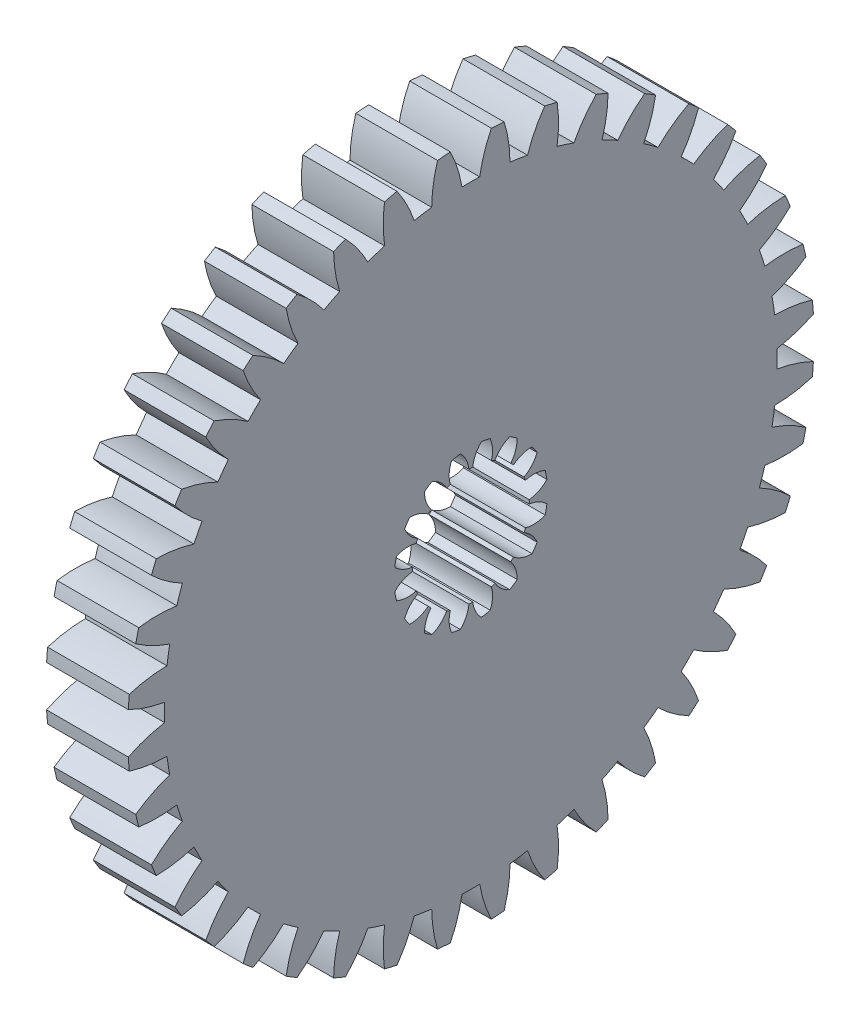
SolidWorks part; units mm, degrees
ref_plane "Plane1" through (0, 0, 0) normal (0, 0, 1) x (1, 0, 0)
ref_plane "Plane2" through (0, 0, 0) normal (0, 1, 0) x (1, 0, 0)
ref_plane "Plane3" through (0, 0, 0) normal (1, 0, 0) x (0, 0, -1)
sketch "HoldingSke" plane through (0, 0, 0) normal (0, 1, 0) x (1, 0, 0)
  line L0 (0, 0) -> (0.766, -0.6428)
  line L1 (-15, 0) -> (100, 0) construction
  line L2 (0, 0) -> (-2.1039, 2.3779)
  line L3 (0, 0) -> (-11.863, 4.5341)
  line L4 (0, 0) -> (6.6156, 5.5511)
  line L5 (0, 0) -> (-46.8476, -17.4728)
  line L6 (0, 0) -> (-4.1448, -2.7965)
  line L7 (-2.1039, 2.3779) -> (8.6586, 51.2059)
  line L8 (-76.2, 54.61) -> (-75.9, 54.61)
  line L9 (-67.7845, 28.3722) -> (-49.3413, 33.142)
  line L10 (-76.2, 71.12) -> (104.1128, 71.12)
  line L11 (0, 0) -> (-5, 0)
  line L12 (-76.2, 101.6) -> (-76.162, 101.6)
  line L13 (24.9733, 27.94) -> (52.9518, 28.4284)
  line L14 (24.9733, 27.94) -> (24.9743, 27.94)
  line L15 (24.9733, 27.94) -> (100.4006, 29.5858)
  line L16 (-63.627, -1) -> (-12.827, -1)
  circle A0 centre (0, 0) radius 1
  circle A1 centre (0, 0) radius 18.749
  circle A2 centre (0, 0) radius 37.5
  circle A3 centre (0, 0) radius 1
  dimension "MHD" = 37.498
  dimension "Hub_dia" = 75
  dimension "Bore" = 2
  dimension "MBD" = 2
  dimension "Num_teeth" = 40
  dimension "Pitch" = 1
  dimension "Overall_len" = 50
  dimension "Show_teeth" = 40
  dimension "Thickness" = 5
  dimension "OAL" = 50.0001
  dimension "T_dim" = 0.3
  dimension "Ap" = 14.5
  dimension "H" = 19.05
  dimension "Pitch_radius" = 180.3128
  dimension "Width" = 5
  dimension "Backlash" = 0.038
  dimension "Addendum_fac" = 1
  dimension "Dedendum_fac" = 1.25
  dimension "Clearance_fac" = 0.25
  dimension "Dedendum_add" = 0.001
  dimension "Module" = 1
sketch "BasProSke" plane through (0, 0, 0) normal (0, 1, 0) x (1, 0, 0)
  line L0 (-10, 0) -> (60, 0) construction
  line L1 (0, 0) -> (0, 21)
  line L2 (0, 0) -> (5, 0)
  line L3 (5, 0) -> (5, 21)
  line L4 (5, 21) -> (0, 21)
  dimension "Thickness" = 5
  dimension "Diameter" = 42
revolve "Base-Revolve" add sketch "BasProSke" angle 360 about L0
sketch "TooCutSke" plane through (0, 0, 0) normal (1, 0, 0) x (0, 0, -1)
  line L1 (0, 0) -> (0, 107) construction
  line L2 (0, 0) -> (-0.8517, 19.9819) construction
  line L3 (0, 0) -> (-3.1363, 39.8509) construction
  line L4 (-0.8517, 19.9819) -> (-1.5682, 19.9255) construction
  arc A0 (0.5419, 18.7412) -> (-0.5419, 18.7412) centre (0, 0) ccw
  arc A1 (1.2681, 20.9871) -> (-1.2681, 20.9871) centre (0, 0) ccw
  circle A2 centre (0, 0) radius 20 construction
  circle A3 centre (0, 0) radius 19.363 construction
  arc A4 (-0.5419, 18.7412) -> (-1.2681, 20.9871) centre (-8.4337, 17.4298) ccw
  arc A5 (1.2681, 20.9871) -> (0.5419, 18.7412) centre (8.4337, 17.4298) ccw
  dimension "Root_dia" = 37.498
  dimension "Overcut_dia" = 42.0508
  dimension "Pitch_dia" = 40
  dimension "Base_dia" = 38.7259
  dimension "Flank_rad" = 8
  dimension "Half_ang" = 4.5
  dimension "Half_CT" = 0.7187
extrude "ToothCut" cut sketch "TooCutSke" along normal through all
fillet "Breaks" [suppressed] radius 0.02
fillet "RootFillets" [suppressed] radius 0.251
pattern_circular "TeethCuts" count 40 every 9 about axis through (-10, 0, 0) along (1, 0, 0) of "ToothCut", "RootFillets", "Breaks"
sketch "HubNeaOneSke" plane through (0, 0, 0) normal (-1, 0, 0) x (0, 0, 1)
  circle A0 centre (0, 0) radius 18.749
  dimension "Diameter" = 37.498
extrude "HubNearOne" [suppressed] add sketch "HubNeaOneSke" along normal blind 45.0001
sketch "HubNeaBotSke" plane through (0, 0, 0) normal (-1, 0, 0) x (0, 0, 1)
  circle A0 centre (0, 0) radius 18.749
  dimension "Diameter" = 37.498
extrude "HubNearBoth" [suppressed] add sketch "HubNeaBotSke" along normal blind 22.5
ref_plane "FarPln" through (5, 0, 0) normal (1, 0, 0) x (0, 0, -1)
sketch "HubFarSke" plane through (5, 0, 0) normal (1, 0, 0) x (0, 0, -1)
  circle A0 centre (0, 0) radius 18.749
  dimension "Diameter" = 37.498
extrude "HubFar" [suppressed] add sketch "HubFarSke" along normal blind 22.5
sketch "BorSke" plane through (0, 0, 0) normal (1, 0, 0) x (0, 0, -1)
  circle A0 centre (0, 0) radius 1
  dimension "Diameter" = 2
extrude "Bore" cut sketch "BorSke" along normal mid plane 100.0001
sketch "KeySke" plane through (0, 0, 0) normal (1, 0, 0) x (0, 0, -1)
  line L0 (-0.4, 0) -> (-0.4, 1.3)
  line L1 (-0.4, 1.3) -> (0.4, 1.3)
  line L2 (0.4, 1.3) -> (0.4, 0)
  line L3 (0, 0) -> (0, 34) construction
  line L4 (-0.4, 0) -> (0.4, 0)
  dimension "Offset" = 1.3
  dimension "Width" = 0.8
extrude "Keyway" [suppressed] cut sketch "KeySke" along normal mid plane 100.0001
pattern_circular "Keyway2" [suppressed] count 2 every 90 about axis through (-10, 0, 0) along (1, 0, 0)
sketch "Schizzo2" plane through (5, 0, 0) normal (1, 0, 0) x (0, 0, -1)
  arc A64 (-0.1172, 3.5721) -> (-0.645, 4.6555) centre (-1.906, 3.3711) ccw
  arc A65 (0.1172, 3.5721) -> (-0.1172, 3.5721) centre (0, 0) ccw
  arc A66 (0.645, 4.6555) -> (0.1172, 3.5721) centre (1.906, 3.3711) ccw
  arc A67 (1.1857, 4.548) -> (0.645, 4.6555) centre (0, 0) ccw
  arc A68 (1.2587, 3.345) -> (1.1857, 4.548) centre (-0.4708, 3.8439) ccw
  arc A69 (1.4753, 3.2553) -> (1.2587, 3.345) centre (0, 0) ccw
  arc A70 (2.3775, 4.0543) -> (1.4753, 3.2553) centre (3.051, 2.3851) ccw
  arc A71 (2.8359, 3.748) -> (2.3775, 4.0543) centre (0, 0) ccw
  arc A72 (2.4429, 2.6087) -> (2.8359, 3.748) centre (1.036, 3.7314) ccw
  arc A73 (2.6087, 2.4429) -> (2.4429, 2.6087) centre (0, 0) ccw
  arc A74 (3.748, 2.8359) -> (2.6087, 2.4429) centre (3.7314, 1.036) ccw
  arc A75 (4.0543, 2.3775) -> (3.748, 2.8359) centre (0, 0) ccw
  arc A76 (3.2553, 1.4753) -> (4.0543, 2.3775) centre (2.3851, 3.051) ccw
  arc A77 (3.345, 1.2587) -> (3.2553, 1.4753) centre (0, 0) ccw
  arc A78 (4.548, 1.1857) -> (3.345, 1.2587) centre (3.8439, -0.4708) ccw
  arc A79 (4.6555, 0.645) -> (4.548, 1.1857) centre (0, 0) ccw
  arc A80 (3.5721, 0.1172) -> (4.6555, 0.645) centre (3.3711, 1.906) ccw
  arc A81 (3.5721, -0.1172) -> (3.5721, 0.1172) centre (0, 0) ccw
  arc A82 (4.6555, -0.645) -> (3.5721, -0.1172) centre (3.3711, -1.906) ccw
  arc A83 (4.548, -1.1857) -> (4.6555, -0.645) centre (0, 0) ccw
  arc A84 (3.345, -1.2587) -> (4.548, -1.1857) centre (3.8439, 0.4708) ccw
  arc A85 (3.2553, -1.4753) -> (3.345, -1.2587) centre (0, 0) ccw
  arc A86 (4.0543, -2.3775) -> (3.2553, -1.4753) centre (2.3851, -3.051) ccw
  arc A87 (3.748, -2.8359) -> (4.0543, -2.3775) centre (0, 0) ccw
  arc A88 (2.6087, -2.4429) -> (3.748, -2.8359) centre (3.7314, -1.036) ccw
  arc A89 (2.4429, -2.6087) -> (2.6087, -2.4429) centre (0, 0) ccw
  arc A90 (2.8359, -3.748) -> (2.4429, -2.6087) centre (1.036, -3.7314) ccw
  arc A91 (2.3775, -4.0543) -> (2.8359, -3.748) centre (0, 0) ccw
  arc A92 (1.4753, -3.2553) -> (2.3775, -4.0543) centre (3.051, -2.3851) ccw
  arc A93 (1.2587, -3.345) -> (1.4753, -3.2553) centre (0, 0) ccw
  arc A94 (1.1857, -4.548) -> (1.2587, -3.345) centre (-0.4708, -3.8439) ccw
  arc A95 (0.645, -4.6555) -> (1.1857, -4.548) centre (0, 0) ccw
  arc A96 (0.1172, -3.5721) -> (0.645, -4.6555) centre (1.906, -3.3711) ccw
  arc A97 (-0.1172, -3.5721) -> (0.1172, -3.5721) centre (0, 0) ccw
  arc A98 (-0.645, -4.6555) -> (-0.1172, -3.5721) centre (-1.906, -3.3711) ccw
  arc A99 (-1.1857, -4.548) -> (-0.645, -4.6555) centre (0, 0) ccw
  arc A100 (-1.2587, -3.345) -> (-1.1857, -4.548) centre (0.4708, -3.8439) ccw
  arc A101 (-1.4753, -3.2553) -> (-1.2587, -3.345) centre (0, 0) ccw
  arc A102 (-2.3775, -4.0543) -> (-1.4753, -3.2553) centre (-3.051, -2.3851) ccw
  arc A103 (-2.8359, -3.748) -> (-2.3775, -4.0543) centre (0, 0) ccw
  arc A104 (-2.4429, -2.6087) -> (-2.8359, -3.748) centre (-1.036, -3.7314) ccw
  arc A105 (-2.6087, -2.4429) -> (-2.4429, -2.6087) centre (0, 0) ccw
  arc A106 (-3.748, -2.8359) -> (-2.6087, -2.4429) centre (-3.7314, -1.036) ccw
  arc A107 (-4.0543, -2.3775) -> (-3.748, -2.8359) centre (0, 0) ccw
  arc A108 (-3.2553, -1.4753) -> (-4.0543, -2.3775) centre (-2.3851, -3.051) ccw
  arc A109 (-3.345, -1.2587) -> (-3.2553, -1.4753) centre (0, 0) ccw
  arc A110 (-4.548, -1.1857) -> (-3.345, -1.2587) centre (-3.8439, 0.4708) ccw
  arc A111 (-4.6555, -0.645) -> (-4.548, -1.1857) centre (0, 0) ccw
  arc A112 (-3.5721, -0.1172) -> (-4.6555, -0.645) centre (-3.3711, -1.906) ccw
  arc A113 (-3.5721, 0.1172) -> (-3.5721, -0.1172) centre (0, 0) ccw
  arc A114 (-4.6555, 0.645) -> (-3.5721, 0.1172) centre (-3.3711, 1.906) ccw
  arc A115 (-4.548, 1.1857) -> (-4.6555, 0.645) centre (0, 0) ccw
  arc A116 (-3.345, 1.2587) -> (-4.548, 1.1857) centre (-3.8439, -0.4708) ccw
  arc A117 (-3.2553, 1.4753) -> (-3.345, 1.2587) centre (0, 0) ccw
  arc A118 (-4.0543, 2.3775) -> (-3.2553, 1.4753) centre (-2.3851, 3.051) ccw
  arc A119 (-3.748, 2.8359) -> (-4.0543, 2.3775) centre (0, 0) ccw
  arc A120 (-2.6087, 2.4429) -> (-3.748, 2.8359) centre (-3.7314, 1.036) ccw
  arc A121 (-2.4429, 2.6087) -> (-2.6087, 2.4429) centre (0, 0) ccw
  arc A122 (-2.8359, 3.748) -> (-2.4429, 2.6087) centre (-1.036, 3.7314) ccw
  arc A123 (-2.3775, 4.0543) -> (-2.8359, 3.748) centre (0, 0) ccw
  arc A124 (-1.4753, 3.2553) -> (-2.3775, 4.0543) centre (-3.051, 2.3851) ccw
  arc A125 (-1.2587, 3.345) -> (-1.4753, 3.2553) centre (0, 0) ccw
  arc A126 (-1.1857, 4.548) -> (-1.2587, 3.345) centre (0.4708, 3.8439) ccw
  arc A127 (-0.645, 4.6555) -> (-1.1857, 4.548) centre (0, 0) ccw
  arc A128 (-0.1172, 3.5721) -> (-0.645, 4.6555) centre (-1.906, 3.3711) ccw
  arc A129 (0.1172, 3.5721) -> (-0.1172, 3.5721) centre (0, 0) ccw
  arc A130 (0.645, 4.6555) -> (0.1172, 3.5721) centre (1.906, 3.3711) ccw
  arc A131 (1.1857, 4.548) -> (0.645, 4.6555) centre (0, 0) ccw
  arc A132 (1.2587, 3.345) -> (1.1857, 4.548) centre (-0.4708, 3.8439) ccw
  arc A133 (1.4753, 3.2553) -> (1.2587, 3.345) centre (0, 0) ccw
  arc A134 (2.3775, 4.0543) -> (1.4753, 3.2553) centre (3.051, 2.3851) ccw
  arc A135 (2.8359, 3.748) -> (2.3775, 4.0543) centre (0, 0) ccw
  arc A136 (2.4429, 2.6087) -> (2.8359, 3.748) centre (1.036, 3.7314) ccw
  arc A137 (2.6087, 2.4429) -> (2.4429, 2.6087) centre (0, 0) ccw
  arc A138 (3.748, 2.8359) -> (2.6087, 2.4429) centre (3.7314, 1.036) ccw
  arc A139 (4.0543, 2.3775) -> (3.748, 2.8359) centre (0, 0) ccw
  arc A140 (3.2553, 1.4753) -> (4.0543, 2.3775) centre (2.3851, 3.051) ccw
  arc A141 (3.345, 1.2587) -> (3.2553, 1.4753) centre (0, 0) ccw
  arc A142 (4.548, 1.1857) -> (3.345, 1.2587) centre (3.8439, -0.4708) ccw
  arc A143 (4.6555, 0.645) -> (4.548, 1.1857) centre (0, 0) ccw
  arc A144 (3.5721, 0.1172) -> (4.6555, 0.645) centre (3.3711, 1.906) ccw
  arc A145 (3.5721, -0.1172) -> (3.5721, 0.1172) centre (0, 0) ccw
  arc A146 (4.6555, -0.645) -> (3.5721, -0.1172) centre (3.3711, -1.906) ccw
  arc A147 (4.548, -1.1857) -> (4.6555, -0.645) centre (0, 0) ccw
  arc A148 (3.345, -1.2587) -> (4.548, -1.1857) centre (3.8439, 0.4708) ccw
  arc A149 (3.2553, -1.4753) -> (3.345, -1.2587) centre (0, 0) ccw
  arc A150 (4.0543, -2.3775) -> (3.2553, -1.4753) centre (2.3851, -3.051) ccw
  arc A151 (3.748, -2.8359) -> (4.0543, -2.3775) centre (0, 0) ccw
  arc A152 (2.6087, -2.4429) -> (3.748, -2.8359) centre (3.7314, -1.036) ccw
  arc A153 (2.4429, -2.6087) -> (2.6087, -2.4429) centre (0, 0) ccw
  arc A154 (2.8359, -3.748) -> (2.4429, -2.6087) centre (1.036, -3.7314) ccw
  arc A155 (2.3775, -4.0543) -> (2.8359, -3.748) centre (0, 0) ccw
  arc A156 (1.4753, -3.2553) -> (2.3775, -4.0543) centre (3.051, -2.3851) ccw
  arc A157 (1.2587, -3.345) -> (1.4753, -3.2553) centre (0, 0) ccw
  arc A158 (1.1857, -4.548) -> (1.2587, -3.345) centre (-0.4708, -3.8439) ccw
  arc A159 (0.645, -4.6555) -> (1.1857, -4.548) centre (0, 0) ccw
  arc A160 (0.1172, -3.5721) -> (0.645, -4.6555) centre (1.906, -3.3711) ccw
  arc A161 (-0.1172, -3.5721) -> (0.1172, -3.5721) centre (0, 0) ccw
  arc A162 (-0.645, -4.6555) -> (-0.1172, -3.5721) centre (-1.906, -3.3711) ccw
  arc A163 (-1.1857, -4.548) -> (-0.645, -4.6555) centre (0, 0) ccw
  arc A164 (-1.2587, -3.345) -> (-1.1857, -4.548) centre (0.4708, -3.8439) ccw
  arc A165 (-1.4753, -3.2553) -> (-1.2587, -3.345) centre (0, 0) ccw
  arc A166 (-2.3775, -4.0543) -> (-1.4753, -3.2553) centre (-3.051, -2.3851) ccw
  arc A167 (-2.8359, -3.748) -> (-2.3775, -4.0543) centre (0, 0) ccw
  arc A168 (-2.4429, -2.6087) -> (-2.8359, -3.748) centre (-1.036, -3.7314) ccw
  arc A169 (-2.6087, -2.4429) -> (-2.4429, -2.6087) centre (0, 0) ccw
  arc A170 (-3.748, -2.8359) -> (-2.6087, -2.4429) centre (-3.7314, -1.036) ccw
  arc A171 (-4.0543, -2.3775) -> (-3.748, -2.8359) centre (0, 0) ccw
  arc A172 (-3.2553, -1.4753) -> (-4.0543, -2.3775) centre (-2.3851, -3.051) ccw
  arc A173 (-3.345, -1.2587) -> (-3.2553, -1.4753) centre (0, 0) ccw
  arc A174 (-4.548, -1.1857) -> (-3.345, -1.2587) centre (-3.8439, 0.4708) ccw
  arc A175 (-4.6555, -0.645) -> (-4.548, -1.1857) centre (0, 0) ccw
  arc A176 (-3.5721, -0.1172) -> (-4.6555, -0.645) centre (-3.3711, -1.906) ccw
  arc A177 (-3.5721, 0.1172) -> (-3.5721, -0.1172) centre (0, 0) ccw
  arc A178 (-4.6555, 0.645) -> (-3.5721, 0.1172) centre (-3.3711, 1.906) ccw
  arc A179 (-4.548, 1.1857) -> (-4.6555, 0.645) centre (0, 0) ccw
  arc A180 (-3.345, 1.2587) -> (-4.548, 1.1857) centre (-3.8439, -0.4708) ccw
  arc A181 (-3.2553, 1.4753) -> (-3.345, 1.2587) centre (0, 0) ccw
  arc A182 (-4.0543, 2.3775) -> (-3.2553, 1.4753) centre (-2.3851, 3.051) ccw
  arc A183 (-3.748, 2.8359) -> (-4.0543, 2.3775) centre (0, 0) ccw
  arc A184 (-2.6087, 2.4429) -> (-3.748, 2.8359) centre (-3.7314, 1.036) ccw
  arc A185 (-2.4429, 2.6087) -> (-2.6087, 2.4429) centre (0, 0) ccw
  arc A186 (-2.8359, 3.748) -> (-2.4429, 2.6087) centre (-1.036, 3.7314) ccw
  arc A187 (-2.3775, 4.0543) -> (-2.8359, 3.748) centre (0, 0) ccw
  arc A188 (-1.4753, 3.2553) -> (-2.3775, 4.0543) centre (-3.051, 2.3851) ccw
  arc A189 (-1.2587, 3.345) -> (-1.4753, 3.2553) centre (0, 0) ccw
  arc A190 (-1.1857, 4.548) -> (-1.2587, 3.345) centre (0.4708, 3.8439) ccw
  arc A191 (-0.645, 4.6555) -> (-1.1857, 4.548) centre (0, 0) ccw
  dimension "D1" = 0
extrude "Taglio-Estrusione1" cut sketch "Schizzo2" against normal blind 10
equation "' \"Module@HoldingSke\" = 6.35"
equation "' \"Num_teeth@HoldingSke\" = 12"
equation "' \"Ap@HoldingSke\" =  20"
equation "' \"Ap@HoldingSke\" = 20"
equation "' \"Width@HoldingSke\" = 0.5 * 25.4"
equation "' \"Hub_dia@HoldingSke\"= 1 * 25.4"
equation "' \"Hub_dia@HoldingSke\" = 1 * 25.4"
equation "' \"Overall_len@HoldingSke\" = 1.0 * 25.4"
equation "' \"Bore@HoldingSke\" = 0.75 * 25.4"
equation "' \"T_dim@HoldingSke\" = 0.1 * 25.4"
equation "' \"Width@KeySke\" = 0.25 * 25.4"
equation "' \"Show_teeth@HoldingSke\" = 13"
equation "' \"Backlash@HoldingSke\" = 0.009 * 25.4"
equation "' \"Addendum_fac@HoldingSke\" = 1.0"
equation "' \"Dedendum_fac@HoldingSke\" = 1.25"
equation "' \"Dedendum_add@HoldingSke\" = 0.00005 * 25.4"
equation "' \"Clearance_fac@HoldingSke\" = 0.25"
equation "\"Pitch@HoldingSke\" = 1 / \"Module@HoldingSke\""
equation "\"Overcut_dia@TooCutSke\" = (\"Num_teeth@HoldingSke\" + 2 * \"Addendum_fac@HoldingSke\") / \"Pitch@HoldingSke\" + 0.002 * 25.4"
equation "\"Pitch_dia@TooCutSke\" = \"Num_teeth@HoldingSke\" / \"Pitch@HoldingSke\""
equation "\"Base_dia@TooCutSke\" = \"Num_teeth@HoldingSke\" / \"Pitch@HoldingSke\" * cos((\"Ap@HoldingSke\"  * 3.14159265 / 180))"
equation "\"Root_dia@TooCutSke\" = (\"Num_teeth@HoldingSke\" + 2) / \"Pitch@HoldingSke\" - 2 * (\"Addendum_fac@HoldingSke\" + \"Dedendum_fac@HoldingSke\") / \"Pitch@HoldingSke\" - \"Dedendum_add@HoldingSke\" * 2"
equation "\"Half_ang@TooCutSke\" = 180 / \"Num_teeth@HoldingSke\""
equation "\"Half_CT@TooCutSke\" = \"Num_teeth@HoldingSke\" / \"Pitch@HoldingSke\" * sin((3.14159265 / 2 / \"Num_teeth@HoldingSke\")) / 2 - 7 * \"Backlash@HoldingSke\" / 4"
equation "\"Flank_rad@TooCutSke\" = \"Num_teeth@HoldingSke\" / \"Pitch@HoldingSke\" / 5"
equation "\"Radius@RootFillets\" = \"Clearance_fac@HoldingSke\" / \"Pitch@HoldingSke\" + \"Dedendum_add@HoldingSke\""
equation "\"Break_rad@Breaks\" = 0.02 / \"Pitch@HoldingSke\""
equation "\"Thickness@HoldingSke\" = \"Width@HoldingSke\""
equation "\"OAL@HoldingSke\" = \"Thickness@HoldingSke\""
equation "\"MHD@HoldingSke\" = (\"Num_teeth@HoldingSke\" + 2) / \"Pitch@HoldingSke\" - 2 * (\"Addendum_fac@HoldingSke\" + \"Dedendum_fac@HoldingSke\")  / \"Pitch@HoldingSke\" - \"Dedendum_add@HoldingSke\" * 2"
equation "\"MBD@HoldingSke\" = (\"Num_teeth@HoldingSke\" + 2) / \"Pitch@HoldingSke\" - 2 * (\"Addendum_fac@HoldingSke\" + \"Dedendum_fac@HoldingSke\")  / \"Pitch@HoldingSke\" - \"Dedendum_add@HoldingSke\" * 2 - 0.002 * 25.4"
equation "\"MHD@HoldingSke\" = ((sgn( \"MHD@HoldingSke\" - \"Hub_dia@HoldingSke\" )-1)*( \"MHD@HoldingSke\" - \"Hub_dia@HoldingSke\" ))/-2+ \"Hub_dia@HoldingSke\""
equation "\"MBD@HoldingSke\" = ((sgn( \"MBD@HoldingSke\" - \"Bore@HoldingSke\" )-1)*( \"MBD@HoldingSke\" - \"Bore@HoldingSke\" ))/-2+ \"Bore@HoldingSke\""
equation "\"OAL@HoldingSke\" = ((sgn( \"OAL@HoldingSke\" - \"Overall_len@HoldingSke\" )+1)*( \"OAL@HoldingSke\" - \"Overall_len@HoldingSke\" ))/2 + \"Overall_len@HoldingSke\" + 0.000002 * 25.4"
equation "\"Num_teeth@TeethCuts\" = int( \"Show_teeth@HoldingSke\" ) + 1"
equation "\"Num_teeth@TeethCuts\" = ((sgn( \"Num_teeth@TeethCuts\" - \"Num_teeth@HoldingSke\" )-1)*( \"Num_teeth@TeethCuts\" - \"Num_teeth@HoldingSke\" ))/-2+ \"Num_teeth@HoldingSke\""
equation "\"Num_teeth@TeethCuts\" = ((sgn( \"Num_teeth@TeethCuts\" - 2.0)+1)*( \"Num_teeth@TeethCuts\" - 2.0))/2 +2.0"
equation "\"Angle@TeethCuts\" = 360.0 / \"Num_teeth@HoldingSke\""
equation "\"Diameter@BasProSke\" = (\"Num_teeth@HoldingSke\" + 2 * \"Addendum_fac@HoldingSke\") / \"Pitch@HoldingSke\""
equation "\"Thickness@BasProSke\"  = \"Thickness@HoldingSke\""
equation "' \"Fillet_rad@BasProSke\" =  \"Thickness@HoldingSke\" * 0.05"
equation "' \"Fillet_rad@BasProSke\" = \"Thickness@HoldingSke\" * 0.05"
equation "\"MHD@HoldingSke\" = ((sgn( \"MHD@HoldingSke\" - \"Root_dia@TooCutSke\" )-1)*( \"MHD@HoldingSke\" - \"Root_dia@TooCutSke\" ))/-2+ \"Root_dia@TooCutSke\""
equation "\"Diameter@HubNeaOneSke\" = \"MHD@HoldingSke\""
equation "\"Length@HubNearOne\" = \"OAL@HoldingSke\" - \"Thickness@BasProSke\""
equation "\"Diameter@HubNeaBotSke\" = \"MHD@HoldingSke\""
equation "\"Length@HubNearBoth\" = ( \"OAL@HoldingSke\" - \"Thickness@BasProSke\" ) / 2.0"
equation "\"Thickness@FarPln\" = \"Thickness@BasProSke\""
equation "\"Diameter@HubFarSke\" = \"MHD@HoldingSke\""
equation "\"Length@HubFar\" = ( \"OAL@HoldingSke\" - \"Thickness@BasProSke\" ) / 2.0"
equation "\"Diameter@BorSke\" = \"MBD@HoldingSke\""
equation "\"D1@Bore\" = \"OAL@HoldingSke\" * 2.0"
equation "\"D1@Keyway\" = \"OAL@HoldingSke\" * 2.0"
equation "\"Offset@KeySke\" = \"T_dim@HoldingSke\" + \"MBD@HoldingSke\" / 2.0"
